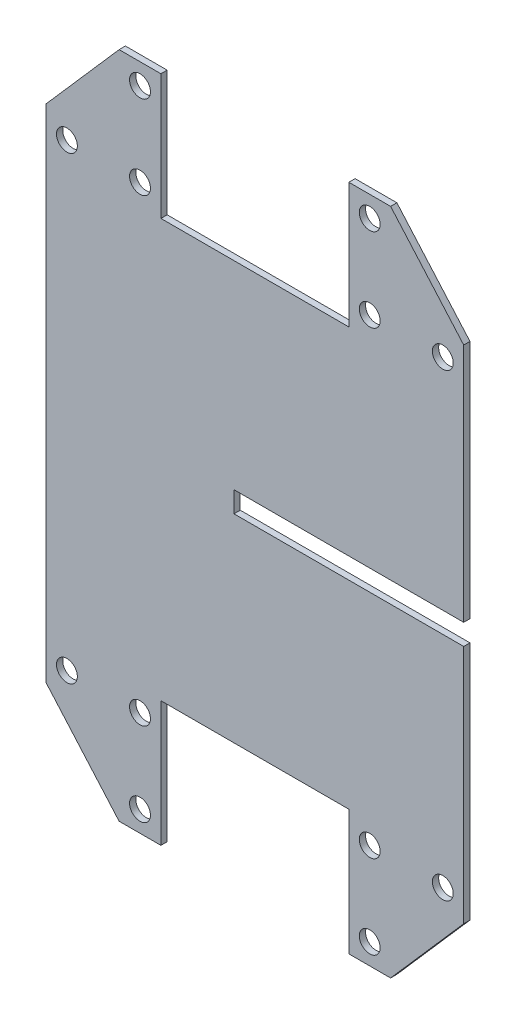
SolidWorks part; units mm, degrees
ref_plane "Plan de face" through (0, 0, 0) normal (0, 0, 1) x (1, 0, 0)
ref_plane "Plan de dessus" through (0, 0, 0) normal (0, 1, 0) x (1, 0, 0)
ref_plane "Plan de droite" through (0, 0, 0) normal (1, 0, 0) x (0, 0, -1)
sketch "Esquisse1" plane through (0, 0, 0) normal (0, 0, 1) x (1, 0, 0)
  line L1 (0, 100) -> (200, 100)
  line L2 (0, 100) -> (0, 0)
  line L3 (0, 0) -> (200, 0)
  line L4 (200, 100) -> (200, 0)
  line L5 (0, 100) -> (55, 100)
  line L6 (0, 100) -> (0, 160)
  line L7 (0, 160) -> (55, 160)
  line L8 (55, 100) -> (55, 160)
  line L9 (200, 100) -> (145, 100)
  line L10 (200, 100) -> (200, 160)
  line L11 (200, 160) -> (145, 160)
  line L12 (145, 100) -> (145, 160)
  line L13 (200, 0) -> (90, 0)
  line L14 (200, 0) -> (200, 5)
  line L15 (200, 5) -> (90, 5)
  line L16 (90, 0) -> (90, 5)
  line L18 (200, 100) -> (200, 80)
  line L21 (200, 120) -> (180, 120) construction
  line L22 (180, 120) -> (180, 100) construction
  line L23 (180, 120) -> (200, 100) construction
  line L24 (0, 120) -> (20, 120) construction
  line L25 (20, 120) -> (20, 100) construction
  line L26 (0, 100) -> (20, 120) construction
  line L27 (35, 160) -> (35, 100) construction
  line L28 (35, 140) -> (55, 140) construction
  line L29 (55, 120) -> (35, 120) construction
  line L30 (35, 160) -> (55, 140) construction
  line L31 (35, 120) -> (55, 100) construction
  line L32 (165, 160) -> (165, 100) construction
  line L33 (145, 140) -> (165, 140) construction
  line L34 (165, 120) -> (145, 120) construction
  line L35 (145, 160) -> (165, 140) construction
  line L36 (145, 120) -> (165, 100) construction
  line L37 (35, 160) -> (0, 120)
  line L38 (165, 160) -> (200, 120)
  circle A1 centre (190, 110) radius 5
  circle A2 centre (10, 110) radius 5
  circle A3 centre (45, 150) radius 5
  circle A4 centre (45, 110) radius 5
  circle A5 centre (155, 150) radius 5
  circle A6 centre (155, 110) radius 5
  point P24 (190, 110)
  point P31 (10, 110)
  point P43 (45, 150)
  point P44 (45, 110)
  point P56 (155, 150)
  point P58 (155, 110)
  dimension "D10" = 10
  dimension "D14" = 10
  dimension "D18" = 10
  dimension "D19" = 10
  dimension "D21" = 10
  dimension "D22" = 10
  dimension "D1" = 200
  dimension "D2" = 100
  dimension "D3" = 90
  dimension "D4" = 60
  dimension "D5" = 110
  dimension "D6" = 5
  dimension "D11" = 20
  dimension "D12" = 20
  dimension "D13" = 20
  dimension "D15" = 20
  dimension "D16" = 20
  dimension "D17" = 20
  dimension "D20" = 20
extrude "Boss.-Extru.1" add sketch "Esquisse1" along normal blind 3
mirror "Symétrie1" about plane through (0, 0, 3) normal (0, 1, 0) of "Boss.-Extru.1"
